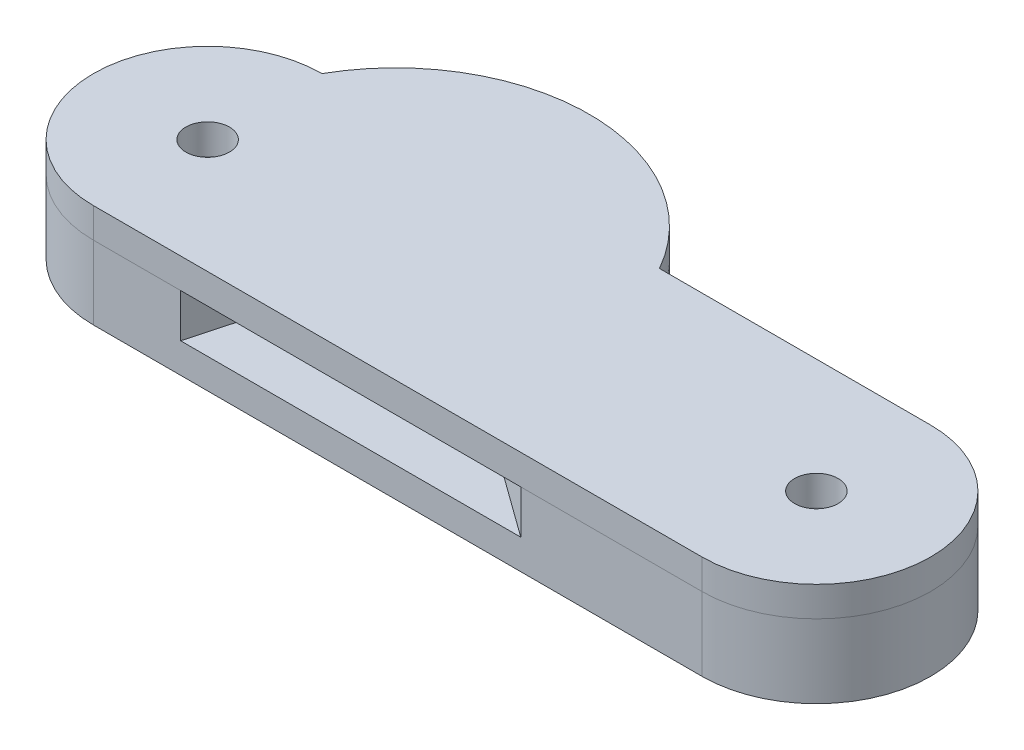
SolidWorks part; units mm, degrees
ref_plane "Front Plane" through (0, 0, 0) normal (0, 0, 1) x (1, 0, 0)
ref_plane "Top Plane" through (0, 0, 0) normal (0, 1, 0) x (1, 0, 0)
ref_plane "Right Plane" through (0, 0, 0) normal (1, 0, 0) x (0, 0, -1)
sketch "Sketch1" plane through (0, 0, 0) normal (0, 1, 0) x (1, 0, 0)
  line L0 (0, -10.5004) -> (-55.9305, -10.5004)
  line L1 (0, 10.5004) -> (-55.9305, 10.5004)
  line L5 (0, 11.5004) -> (-55.9305, 11.5004) construction
  line L6 (0, -11.5004) -> (-55.9305, -11.5004) construction
  circle A0 centre (0, 0) radius 2
  arc A1 (0, -10.5004) -> (0, 10.5004) centre (0, 0) ccw
  arc A2 (-55.9305, 10.5004) -> (-55.9305, -10.5004) centre (-55.9305, 0) ccw
  circle A3 centre (-55.9305, 0) radius 2
  arc A7 (0, -11.5004) -> (0, 11.5004) centre (0, 0) ccw construction
  arc A8 (-55.9305, 11.5004) -> (-55.9305, -11.5004) centre (-55.9305, 0) ccw construction
  arc A9 (-67.2423, -5.04) -> (-54.9145, -15.6487) centre (-55.7741, -4.1805) ccw construction
  arc A10 (-55.9305, 10.5004) -> (-55.9305, -10.5004) centre (-55.9305, 0) ccw construction
  circle A11 centre (0, 0) radius 67.4309 construction
  arc A12 (-59.8966, 30.973) -> (-67.2423, -5.04) centre (0, 0) ccw construction
  dimension "D1" = 4
  dimension "D2" = 1
  dimension "D3" = 4
extrude "Boss-Extrude1" add sketch "Sketch1" along normal mid plane 9.5
sketch "Sketch3" plane through (0, 0, 0) normal (0, 1, 0) x (1, 0, 0)
  line L0 (0, 0) -> (-47.1525, -15.3208) construction
  line L1 (0, 0) -> (24.7895, -42.9367) construction
  line L2 (0, 0) -> (-55.9305, 0) construction
  line L3 (24.7895, -42.9367) -> (-41.5934, 5.0595) construction
  line L4 (-41.5934, 5.0595) -> (-47.1525, -15.3208) construction
  line L5 (-41.5934, 5.0595) -> (-37.6461, 19.5308) construction
  line L6 (-41.5934, 5.0595) -> (-53.749, 13.8482) construction
  line L7 (22.8477, -44.0007) -> (-38.0092, 0) construction
  line L8 (-35.7518, 18.8753) -> (-39.2995, 5.869)
  line L9 (-43.8873, 4.25) -> (-54.8123, 12.149)
  line L11 (26.6452, -41.8104) -> (-39.2995, 5.869)
  line L12 (-39.6108, 19.9279) -> (-42.7627, 8.3729) construction
  line L13 (-42.7627, 8.3729) -> (-52.4686, 15.3905) construction
  line L14 (-40.9004, 0) -> (-45.9674, -18.5763) construction
  line L15 (-43.8873, 4.25) -> (-48.2065, -11.585)
  line L18 (-40.4216, 6.6802) -> (-50.8477, 14.2185) construction
  line L20 (-41.5934, 5.0595) -> (-52.0196, 12.5978) construction
  line L21 (-42.7652, 3.4387) -> (-53.1914, 10.977) construction
  line L23 (-43.5229, 5.5858) -> (-49.082, -14.7945) construction
  line L26 (-39.6639, 4.5332) -> (-45.223, -15.8471) construction
  line L27 (25.9613, -41.316) -> (-40.4216, 6.6802) construction
  line L28 (23.6177, -44.5574) -> (-42.7652, 3.4387) construction
  arc A1 (-48.2065, -11.585) -> (26.6452, -41.8104) centre (0, 0) ccw
  arc A4 (-55.9305, 10.5004) -> (-55.9305, -10.5004) centre (-55.9305, 0) ccw construction
  arc A7 (-35.7518, 18.8753) -> (-54.8123, 12.149) centre (-41.5934, 5.0595) ccw
  dimension "D1" = 99.1581
  dimension "D3" = 120
  dimension "D6" = 30
  dimension "D2" = 18
  dimension "D4" = 2
  dimension "D5" = 2
extrude "Cut-Extrude1" cut sketch "Sketch3" against normal mid plane 4
sketch "Sketch5" plane through (0, 0, 0) normal (0, 1, 0) x (1, 0, 0)
  line L0 (-40.4241, 1.7461) -> (-52.5322, 10.5004) construction
  line L1 (-40.4241, 1.7461) -> (-35.7382, 18.9254) construction
  line L2 (-52.5322, 10.5004) -> (-43.8873, 4.25) construction
  line L3 (-39.2995, 5.869) -> (-38.0362, 10.5004) construction
  line L4 (-55.9305, 10.5004) -> (-24.9177, 10.5004)
  line L5 (0, 10.5004) -> (-55.9305, 10.5004) construction
  circle A0 centre (-40.4241, 1.7461) radius 17.807
extrude "Boss-Extrude2" add sketch "Sketch5" along normal up to surface and the other way up to surface
sketch "Sketch6" plane through (0, 0, 0) normal (0, 1, 0) x (1, 0, 0)
  line L0 (-39.2995, 5.869) -> (-16.6593, -10.5004)
  line L1 (-47.9107, -10.5004) -> (-43.8873, 4.25)
  line L2 (-43.8873, 4.25) -> (-54.8544, 12.1794)
  line L3 (-39.2995, 5.869) -> (-35.7382, 18.9254)
  line L4 (-16.6593, -10.5004) -> (-39.2995, 5.869) construction
  line L5 (-43.8873, 4.25) -> (-47.9107, -10.5004) construction
  line L6 (-52.5322, 10.5004) -> (-43.8873, 4.25) construction
  line L7 (-39.2995, 5.869) -> (-38.0362, 10.5004) construction
  line L8 (-55.9305, -10.5004) -> (0, -10.5004) construction
  line L9 (-16.6593, -10.5004) -> (-47.9107, -10.5004)
  arc A0 (-24.9177, 10.5004) -> (-55.9305, 10.5004) centre (-40.4241, 1.7461) ccw construction
  arc A1 (-35.7382, 18.9254) -> (-54.8544, 12.1794) centre (-40.4241, 1.7461) ccw
extrude "Cut-Extrude2" cut sketch "Sketch6" against normal mid plane 4
ref_plane "Plane1" through (0, 2, 0) normal (0, -1, 0) x (-1, 0, 0)
split "Split1" trim tools "Plane1" bodies to split 105 resulting bodies 106 107
